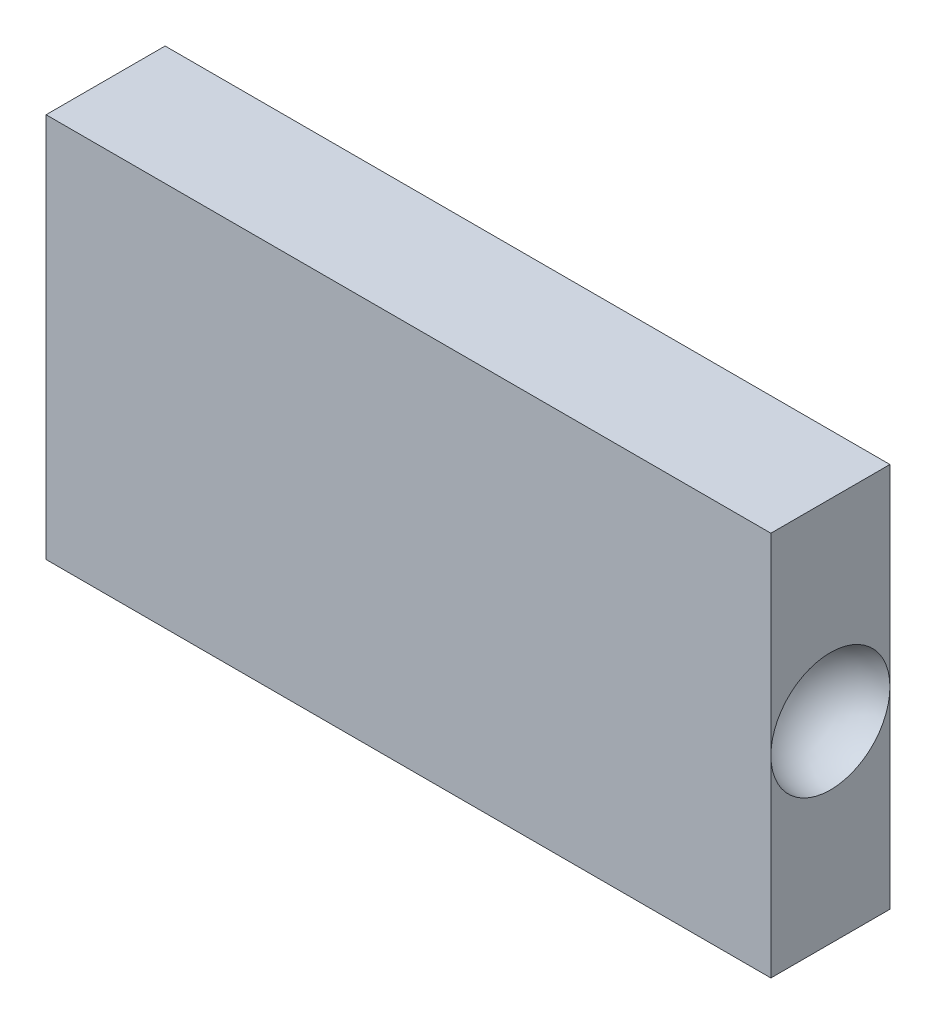
SolidWorks part; units mm, degrees
ref_plane "前视基准面" through (0, 0, 0) normal (0, 0, 1) x (1, 0, 0)
ref_plane "上视基准面" through (0, 0, 0) normal (0, 1, 0) x (1, 0, 0)
ref_plane "右视基准面" through (0, 0, 0) normal (1, 0, 0) x (0, 0, -1)
other "Configuration Table"
sketch "草图2" plane through (0, 0, 0) normal (0, 0, 1) x (1, 0, 0)
  line L1 (-30.4443, 16.18) -> (30.4443, 16.18)
  line L2 (-30.4443, 16.18) -> (-30.4443, -16.18)
  line L3 (-30.4443, -16.18) -> (30.4443, -16.18)
  line L4 (30.4443, 16.18) -> (30.4443, -16.18)
  line L5 (-30.4443, 16.18) -> (30.4443, -16.18) construction
  line L6 (-30.4443, -16.18) -> (30.4443, 16.18) construction
  point P0 (0, 0)
extrude "凸台-拉伸1" add sketch "草图2" along normal blind 10
sketch "草图5" plane through (0, 0, 0) normal (0, 1, 0) x (1, 0, 0)
  line L0 (-30.4443, -10) -> (-30.4443, 0) construction
  line L1 (-30.4443, 0) -> (-30.4443, -10)
  arc A0 (-30.4443, -10) -> (-30.4443, 0) centre (-30.4443, -5) ccw
revolve "切除-旋转5" cut sketch "草图5" angle 360 about L1
mirror "镜向1" about plane through (0, 0, 0) normal (1, 0, 0) of "切除-旋转5"
sketch "草图6" plane through (0, 0, 0) normal (0, 1, 0) x (1, 0, 0)
  line L0 (-4.9139, 0) -> (4.9139, 0)
  arc A0 (-4.9139, 0) -> (4.9139, 0) centre (0, 0) ccw
revolve "切除-旋转6" cut sketch "草图6" angle 360 about L0
